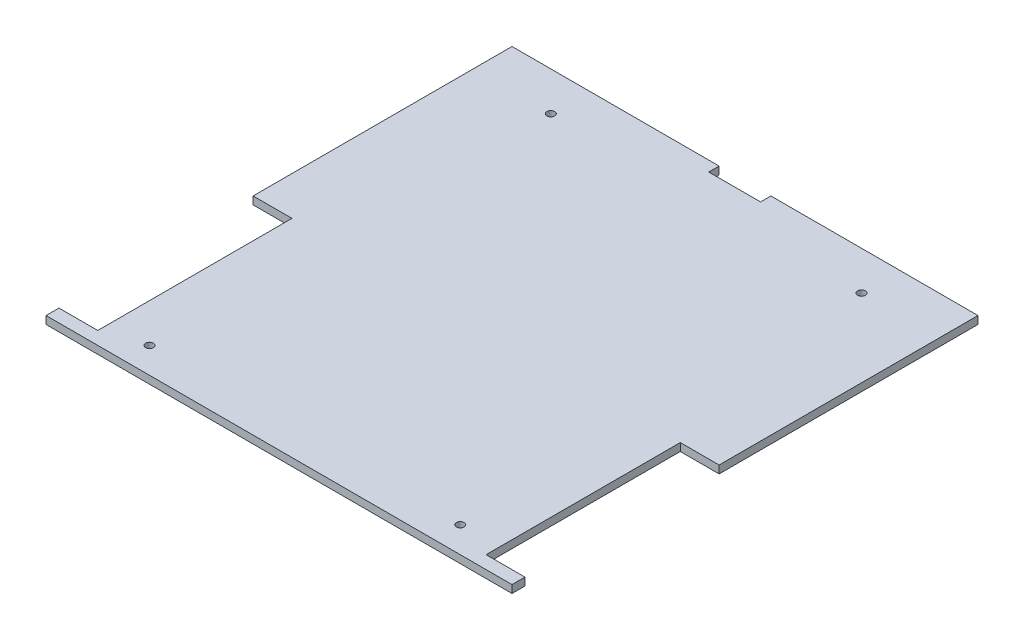
SolidWorks part; units mm, degrees
ref_plane "Front Plane" through (0, 0, 0) normal (0, 0, 1) x (1, 0, 0)
ref_plane "Top Plane" through (0, 0, 0) normal (0, 1, 0) x (1, 0, 0)
ref_plane "Right Plane" through (0, 0, 0) normal (1, 0, 0) x (0, 0, -1)
sketch "Sketch1" plane through (0, 0, 0) normal (0, 1, 0) x (1, 0, 0)
  line L1 (-90, 90) -> (90, 90)
  line L6 (-90, 90) -> (-90, -90)
  line L7 (-90, -90) -> (90, -90)
  line L8 (90, 90) -> (90, -90)
  line L9 (-90, 90) -> (90, -90) construction
  line L10 (-90, -90) -> (90, 90) construction
  point P0 (0, 0)
  dimension "D1" = 180
  dimension "D2" = 180
extrude "Boss-Extrude1" add sketch "Sketch1" along normal blind 3
sketch "Sketch2" plane through (0, 3, 0) normal (0, 1, 0) x (1, 0, 0)
  line L0 (-90, 90) -> (-90, -90) construction
  line L5 (-90, -10) -> (-75, -10)
  line L6 (-90, -10) -> (-90, -85)
  line L7 (-90, -85) -> (-75, -85)
  line L8 (-75, -10) -> (-75, -85)
  line L14 (0, 0) -> (0, -94.1115) construction
  line L15 (90, -85) -> (75, -85)
  line L16 (90, -10) -> (90, -85)
  line L17 (75, -10) -> (75, -85)
  line L18 (90, -10) -> (75, -10)
  line L19 (-90, -90) -> (90, -90) construction
  dimension "D1" = 75
  dimension "D2" = 15
  dimension "D3" = 5
extrude "Cut-Extrude1" cut sketch "Sketch2" against normal blind 3
sketch "Sketch3" plane through (0, 3, 0) normal (0, 1, 0) x (1, 0, 0)
  line L0 (-75, -85) -> (-75, -10) construction
  line L2 (0, 0) -> (0, -66.2917) construction
  line L3 (-90, -90) -> (90, -90) construction
  line L4 (-90, 90) -> (-90, -10) construction
  line L5 (90, 90) -> (-90, 90) construction
  circle A8 centre (-60, -80) radius 1.5
  circle A9 centre (60, -80) radius 1.5
  circle A14 centre (-60, 75) radius 1.5
  circle A15 centre (60, 75) radius 1.5
  point P29 (0, 0)
  dimension "D11" = 3
  dimension "D19" = 3
  dimension "D9" = 10
  dimension "D10" = 15
  dimension "D17" = 30
  dimension "D18" = 15
extrude "Cut-Extrude2" cut sketch "Sketch3" against normal blind 3
sketch "Sketch4" plane through (0, 3, 0) normal (0, 1, 0) x (1, 0, 0)
  line L0 (90, 90) -> (-90, 90) construction
  line L1 (-10, 90) -> (10, 90)
  line L2 (-10, 90) -> (-10, 86)
  line L3 (-10, 86) -> (10, 86)
  line L4 (10, 90) -> (10, 86)
  line L5 (-90, 90) -> (-90, -10) construction
  dimension "D1" = 20
  dimension "D2" = 4
  dimension "D3" = 80
extrude "Cut-Extrude3" cut sketch "Sketch4" against normal blind 10
